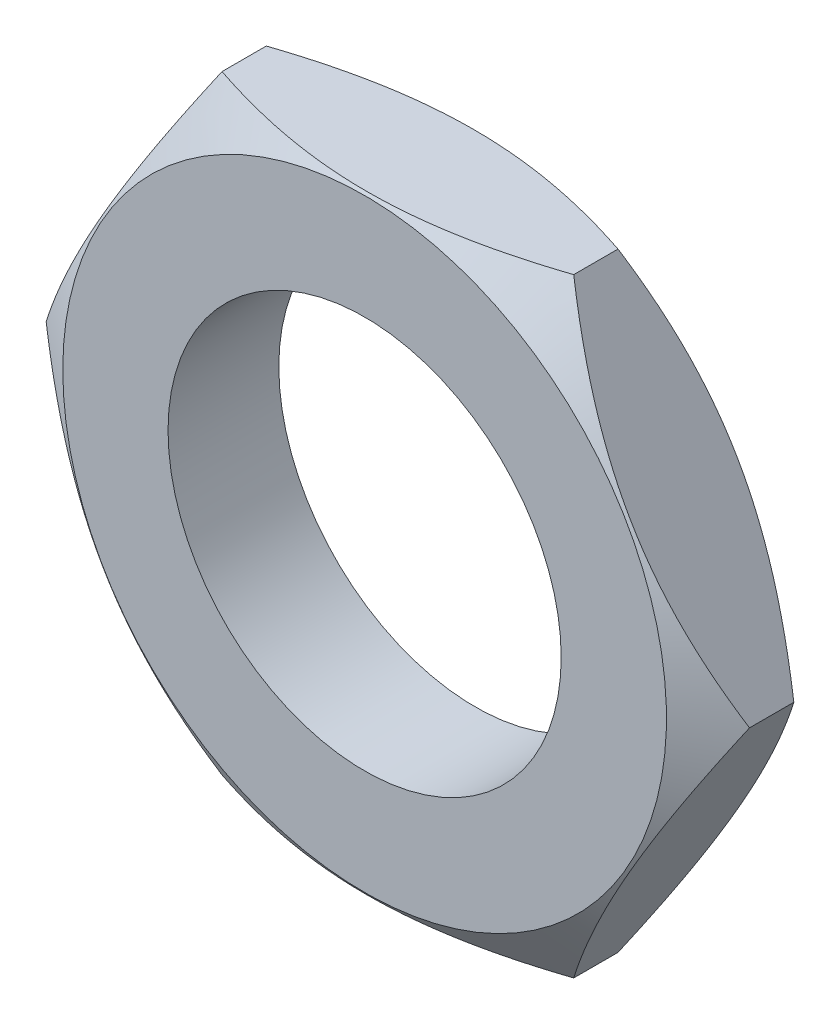
SolidWorks part; units mm, degrees
ref_plane "Plan de face" through (0, 0, 0) normal (0, 0, 1) x (1, 0, 0)
ref_plane "Plan de dessus" through (0, 0, 0) normal (0, 1, 0) x (1, 0, 0)
ref_plane "Plan de droite" through (0, 0, 0) normal (1, 0, 0) x (0, 0, -1)
sketch "Esquisse1" plane through (0, 0, 0) normal (0, 0, 1) x (1, 0, 0)
  line L1 (3.1754, -5.5) -> (6.3509, 0)
  line L2 (6.3509, 0) -> (3.1754, 5.5)
  line L3 (3.1754, 5.5) -> (-3.1754, 5.5)
  line L4 (-3.1754, 5.5) -> (-6.3509, 0)
  line L5 (-6.3509, 0) -> (-3.1754, -5.5)
  line L6 (-3.1754, -5.5) -> (3.1754, -5.5)
  circle A0 centre (0, 0) radius 5.5 construction
  circle A1 centre (0, 0) radius 3.55
  dimension "D1" = 11
  dimension "D2" = 7.1
extrude "Boss.-Extru.1" add sketch "Esquisse1" along normal mid plane 2
sketch "Esquisse2" plane through (0, 0, 0) normal (0, 1, 0) x (1, 0, 0)
  line L0 (-6.3509, -0.4) -> (-5.4509, -1)
  line L1 (-6.3509, -1) -> (-6.3509, 1) construction
  line L3 (-6.3509, -0.4) -> (-6.3509, -1)
  line L4 (-6.3509, -1) -> (-5.4509, -1)
  point P6 (0, 0)
  dimension "D1" = 0.6
  dimension "D2" = 0.9
ref_axis "Axe1" through (0, 0, -0.1) along (0, 0, 1)
revolve "Enlèvement de matière-Révolution1" cut sketch "Esquisse2" angle 360 about axis through (0, 0, -0.1) along (0, 0, 1)
mirror "Symétrie2" about plane through (0, 0, 0) normal (0, 0, 1) of "Enlèvement de matière-Révolution1"
